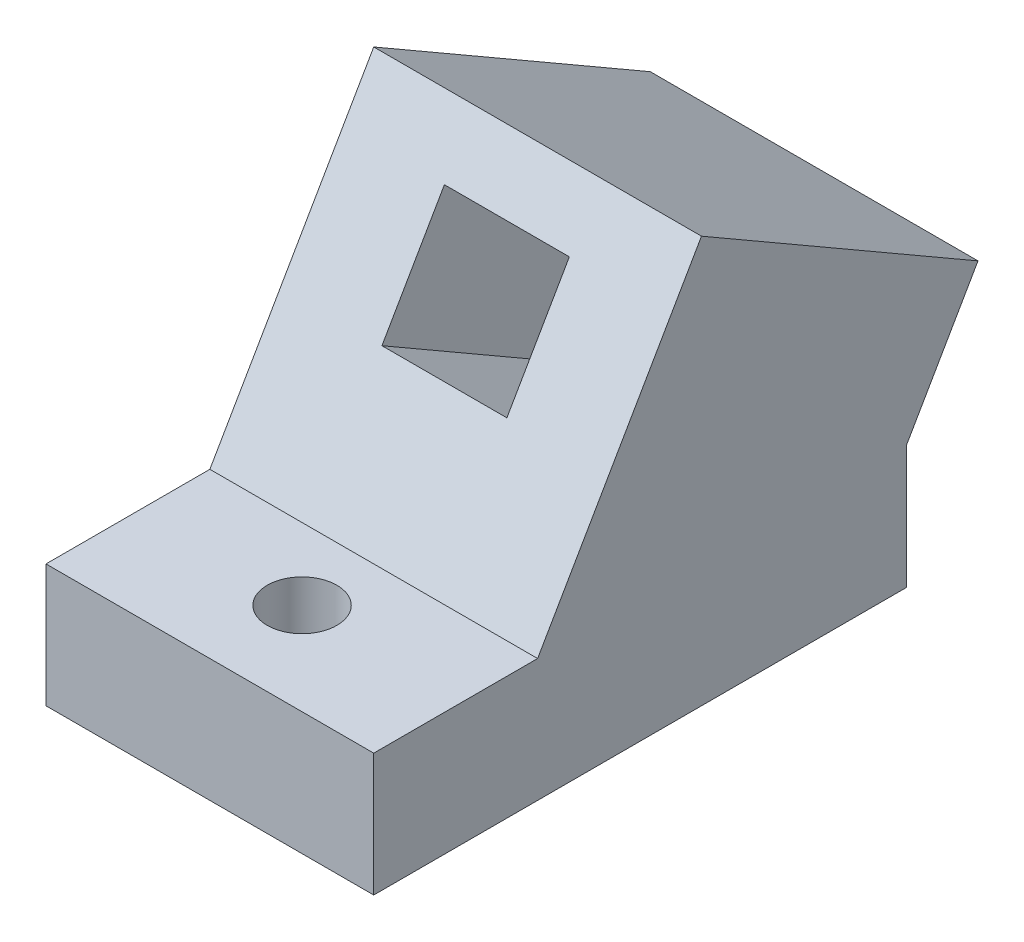
SolidWorks part; units mm, degrees
ref_plane "前视基准面" through (0, 0, 0) normal (0, 0, 1) x (1, 0, 0)
ref_plane "上视基准面" through (0, 0, 0) normal (0, 1, 0) x (1, 0, 0)
ref_plane "右视基准面" through (0, 0, 0) normal (1, 0, 0) x (0, 0, -1)
sketch "草图6" plane through (0, 0, 0) normal (0, 1, 0) x (1, 0, 0)
  line L0 (0, 6.5) -> (8, 6.5) construction
  line L1 (0, 0) -> (8, 0)
  line L2 (0, 0) -> (0, 13)
  line L3 (0, 13) -> (8, 13)
  line L4 (8, 0) -> (8, 13)
  line L5 (4, 13) -> (4, 0) construction
  circle A0 centre (4, 2.25) radius 0.85
  circle A1 centre (4, 10.75) radius 0.85
  dimension "D3" = 1.7
  dimension "D1" = 8
  dimension "D2" = 13
  dimension "D4" = 8.5
extrude "凸台-拉伸1" add sketch "草图6" along normal blind 3
sketch "草图8" plane through (8, 0, 0) normal (1, 0, 0) x (0, 0, -1)
  line L0 (13, 3) -> (14.75, 6.0311)
  line L1 (14.75, 6.0311) -> (8, 9.9282)
  line L2 (8, 9.9282) -> (4, 3)
  line L3 (0, 3) -> (13, 3) construction
  line L8 (0, 0) -> (13, 0)
  line L9 (13, 0) -> (13, 3)
  line L10 (13, 3) -> (0, 3)
  line L11 (0, 3) -> (0, 0)
  line L14 (13, 3) -> (4, 3)
  dimension "D1" = 9
  dimension "D2" = 120
  dimension "D3" = 8
  dimension "D4" = 0
extrude "凸台-拉伸2" add sketch "草图8" against normal up to surface (8 mm away) up to face at (0, 1.5, -6.5)
sketch "草图9" plane through (0, -0.9821, -1.701) normal (0, 0.5, 0.866) x (1, 0, 0)
  line L1 (2.475, 11.0981) -> (5.525, 11.0981)
  line L2 (2.475, 11.0981) -> (2.475, 8.0481)
  line L3 (2.475, 8.0481) -> (5.525, 8.0481)
  line L4 (5.525, 11.0981) -> (5.525, 8.0481)
  line L8 (0, 12.5981) -> (0, 4.5981)
  line L9 (0, 4.5981) -> (8, 4.5981)
  line L10 (8, 4.5981) -> (8, 12.5981)
  line L11 (8, 12.5981) -> (0, 12.5981)
  line L12 (0, 12.5981) -> (0, 4.5981)
  line L13 (0, 4.5981) -> (8, 4.5981)
  line L14 (8, 4.5981) -> (8, 12.5981)
  line L15 (8, 12.5981) -> (0, 12.5981)
  point P10 (4, 11.0981)
  point P11 (4, 12.5981)
  dimension "D1" = 3.05
  dimension "D2" = 3.05
  dimension "D4" = 1.5
  dimension "D3" = 0
extrude "切除-拉伸3" cut sketch "草图9" against normal through all contours L2 L1 L4 L3
